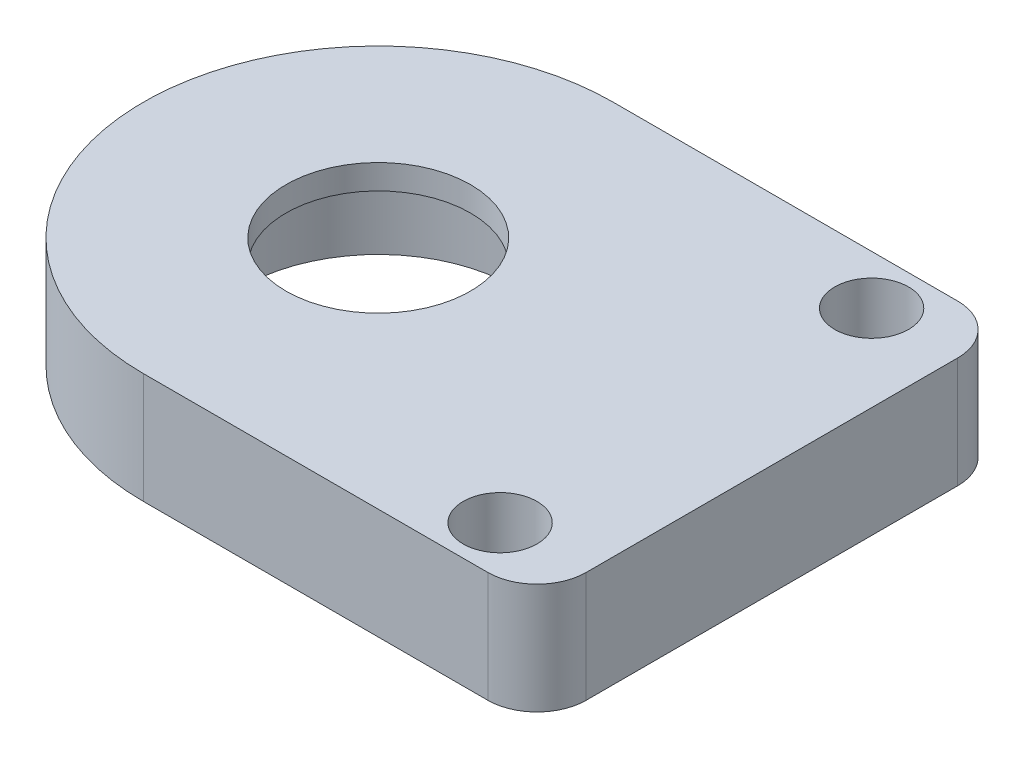
SolidWorks part; units mm, degrees
ref_plane "Ebene vorne" through (0, 0, 0) normal (0, 0, 1) x (1, 0, 0)
ref_plane "Ebene oben" through (0, 0, 0) normal (0, 1, 0) x (1, 0, 0)
ref_plane "Ebene rechts" through (0, 0, 0) normal (1, 0, 0) x (0, 0, -1)
sketch "Skizze1" plane through (0, 0, 0) normal (0, 1, 0) x (1, 0, 0)
  line L0 (0, 19.0986) -> (32, 19.0986)
  line L1 (32, 19.0986) -> (32, -19.0986)
  line L2 (32, -19.0986) -> (0, -19.0986)
  line L3 (0, 0) -> (32, 0) construction
  arc A0 (0, 19.0986) -> (0, -19.0986) centre (0, 0) ccw
  circle A3 centre (25, -15.0986) radius 1.6
  circle A4 centre (25, -15.0986) radius 4 construction
  circle A5 centre (25, 15.0986) radius 4 construction
  circle A6 centre (25, 15.0986) radius 1.6
  circle A7 centre (0, 0) radius 11.075
  dimension "D1" = 38.1972
  dimension "D4" = 8
  dimension "D5" = 3.2
  dimension "D9" = 22.15
  dimension "D2" = 32
  dimension "D6" = 25
extrude "Aufsatz-Linear austragen1" add sketch "Skizze1" along normal blind 7
sketch "Skizze3" plane through (0, 7, 0) normal (0, 1, 0) x (1, 0, 0)
  line L0 (0, -19.0986) -> (32, -19.0986) construction
  line L1 (0, -19.0986) -> (0, 0) construction
  line L2 (0, 0) -> (0, 19.0986) construction
  line L3 (0, 19.0986) -> (32, 19.0986)
  line L4 (32, 19.0986) -> (32, -19.0986)
  line L5 (32, -19.0986) -> (0, -19.0986)
  circle A1 centre (0, 0) radius 7.5
  arc A2 (0, 19.0986) -> (0, -19.0986) centre (0, 0) ccw
  dimension "D1" = 15
extrude "Aufsatz-Linear austragen2" add sketch "Skizze3" along normal blind 2
sketch "Skizze4" plane through (0, 9, 0) normal (0, 1, 0) x (1, 0, 0)
  circle A0 centre (25, 15.0986) radius 3
  circle A1 centre (25, -15.0986) radius 3
  dimension "D1" = 6
  dimension "D2" = 6
extrude "Schnitt-Linear austragen1" cut sketch "Skizze4" against normal blind 6.5
fillet "Verrundung4" radius 4 2 edges at (32, 4.5, -19.0986) (32, 4.5, 19.0986)
